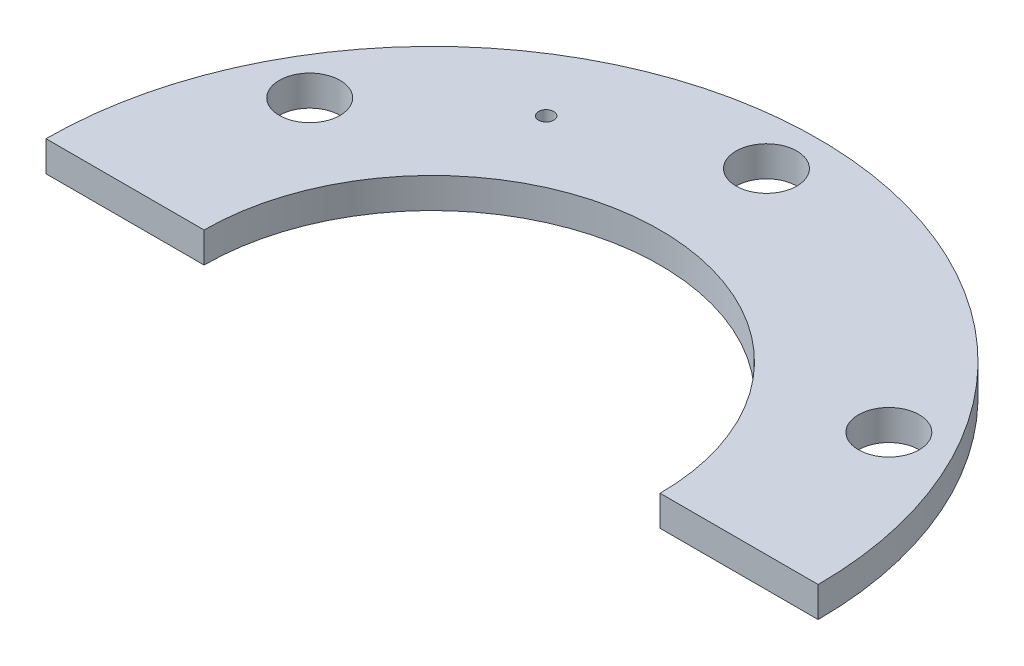
SolidWorks part; units mm, degrees
material "ABS"
ref_plane "Front Plane" through (0, 0, 0) normal (0, 0, 1) x (1, 0, 0)
ref_plane "Top Plane" through (0, 0, 0) normal (0, 1, 0) x (1, 0, 0)
ref_plane "Right Plane" through (0, 0, 0) normal (1, 0, 0) x (0, 0, -1)
sketch "Sketch1" plane through (0, 0, 0) normal (0, 1, 0) x (1, 0, 0)
  circle A0 centre (0, 0) radius 12.7
  dimension "D1" = 25.4
extrude "Boss-Extrude1" add sketch "Sketch1" along normal blind 1
sketch "Sketch19" plane through (0, 1, 0) normal (0, 1, 0) x (1, 0, 0)
  circle A0 centre (0, 11) radius 1
  circle A1 centre (9.5263, 5.5) radius 1
  circle A2 centre (9.5263, -5.5) radius 1
  circle A3 centre (0, -11) radius 1
  circle A4 centre (-9.5263, -5.5) radius 1
  circle A5 centre (-9.5263, 5.5) radius 1
  point P13 (0, 0)
  dimension "D1" = 2
  dimension "D2" = 11
  dimension "D3" = 6
extrude "Cut-Extrude1" cut sketch "Sketch19" against normal through all both and the other way through all
sketch "Sketch20" plane through (0, 1, 0) normal (0, 1, 0) x (1, 0, 0)
  circle A0 centre (0, 0) radius 7.5
  dimension "D1" = 15
extrude "Cut-Extrude2" cut sketch "Sketch20" against normal through all both and the other way through all
sketch "Sketch21" plane through (0, 0, 0) normal (0, 0, 1) x (1, 0, 0)
  line L1 (-36.7533, 32.3113) -> (29.1209, 32.3113)
  line L2 (-36.7533, 32.3113) -> (-36.7533, -19.668)
  line L3 (-36.7533, -19.668) -> (29.1209, -19.668)
  line L4 (29.1209, 32.3113) -> (29.1209, -19.668)
extrude "Cut-Extrude3" cut sketch "Sketch21" along normal through all
sketch "Sketch22" plane through (0, 1, 0) normal (0, 1, 0) x (1, 0, 0)
  line L0 (-9.5263, 5.5) -> (0, 11)
  line L1 (-5.125, 8.8768) -> (0, 0) construction
  circle A0 centre (-5.125, 8.8768) radius 0.25
  point P7 (-4.7631, 8.25)
  dimension "D1" = 0.5
  dimension "D2" = 10.25
  dimension "D3" = 0
extrude "Cut-Extrude4" cut sketch "Sketch22" against normal through all both and the other way through all
